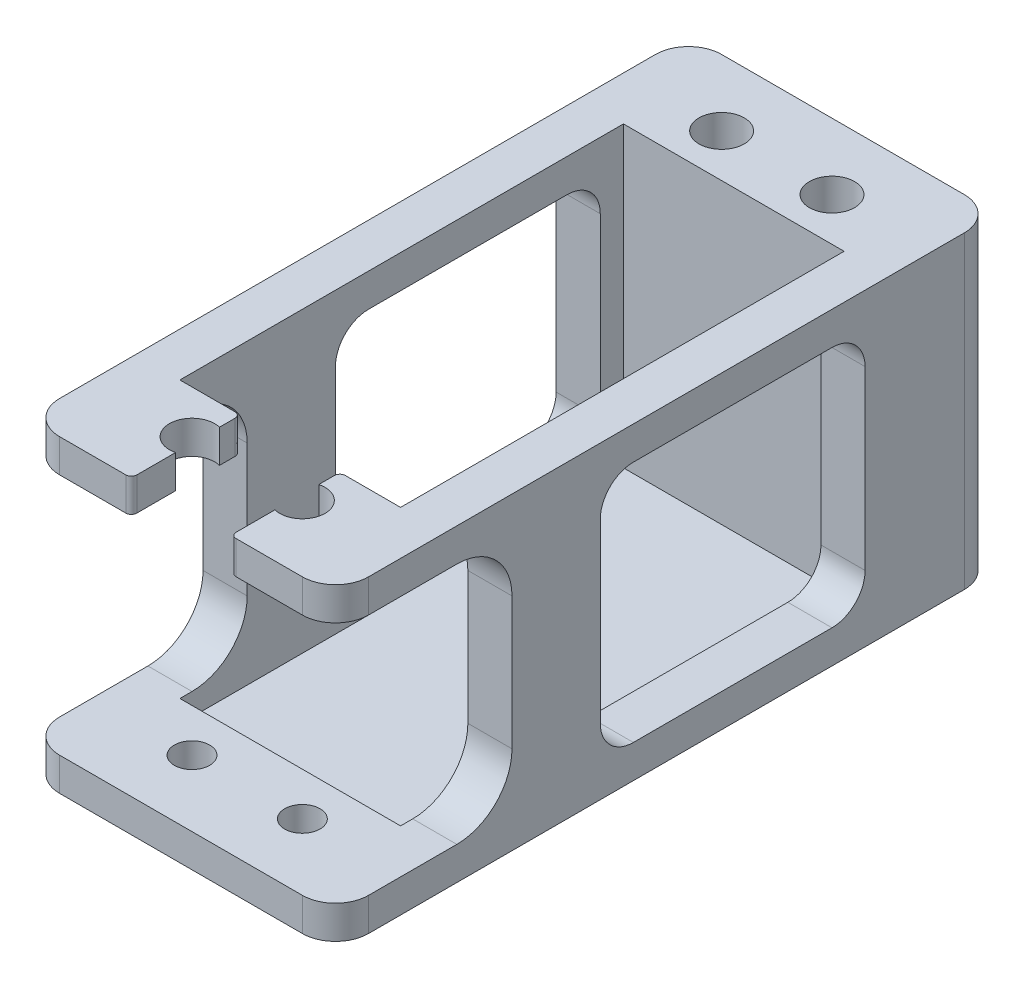
SolidWorks part; units mm, degrees
ref_plane "前视基准面" through (0, 0, 0) normal (0, 0, 1) x (1, 0, 0)
ref_plane "上视基准面" through (0, 0, 0) normal (0, 1, 0) x (1, 0, 0)
ref_plane "右视基准面" through (0, 0, 0) normal (1, 0, 0) x (0, 0, -1)
sketch "草图1" plane through (0, 0, 0) normal (0, 1, 0) x (1, 0, 0)
  line L0 (0, 0) -> (0, 29.0913) construction
  line L5 (-10, 10.2) -> (-10, -30)
  line L6 (-5, 14.1) -> (5, 14.1) construction
  line L7 (-5, 14.1) -> (-5, -33.9) construction
  line L8 (-5, -33.9) -> (5, -33.9) construction
  line L9 (5, 14.1) -> (5, -33.9) construction
  line L10 (-5, -9.9) -> (-42.4696, -9.9) construction
  line L11 (10, 10.2) -> (10, -30)
  line L12 (10, 10.2) -> (-10, 10.2)
  line L13 (10, -30) -> (-10, -30)
  line L15 (-14, -39.9) -> (14, -39.9)
  line L16 (-14, -39.9) -> (-14, 20.1)
  line L17 (-14, 20.1) -> (14, 20.1)
  line L18 (14, -39.9) -> (14, 20.1)
  line L19 (-14, -39.9) -> (14, 20.1) construction
  line L20 (-14, 20.1) -> (14, -39.9) construction
  circle A0 centre (-5, 14.1) radius 2.05
  circle A1 centre (5, 14.1) radius 2.05
  circle A2 centre (-5, -33.9) radius 2.05
  circle A3 centre (5, -33.9) radius 2.05
  point P18 (0, -9.9)
  dimension "D1" = 4.1
  dimension "D2" = 14.1
  dimension "D3" = 48
  dimension "D4" = 10
  dimension "D5" = 20
  dimension "D6" = 40.2
  dimension "D7" = 4
  dimension "D8" = 60
extrude "凸台-拉伸1" add sketch "草图1" along normal blind 28
sketch "草图4" plane through (0, 0, 0) normal (1, 0, 0) x (0, 0, -1)
  line L0 (-39.9, 28) -> (-39.9, 0) construction
  line L1 (-39.9, 25) -> (-23.9, 25)
  line L2 (-39.9, 25) -> (-39.9, 3)
  line L3 (-39.9, 3) -> (-23.9, 3)
  line L4 (-23.9, 25) -> (-23.9, 3)
  line L5 (-39.9, 28) -> (20.1, 28) construction
  line L6 (-39.9, 0) -> (20.1, 0) construction
  line L7 (20.1, 28) -> (20.1, 0) construction
  line L8 (-12.9, 25) -> (5.1, 25)
  line L9 (-15.9, 22) -> (-15.9, 6)
  line L10 (-12.9, 3) -> (5.1, 3)
  line L11 (8.1, 22) -> (8.1, 6)
  arc A0 (5.1, 25) -> (8.1, 22) centre (5.1, 22) cw
  arc A1 (-15.9, 6) -> (-12.9, 3) centre (-12.9, 6) ccw
  arc A2 (5.1, 3) -> (8.1, 6) centre (5.1, 6) ccw
  arc A3 (-12.9, 25) -> (-15.9, 22) centre (-12.9, 22) ccw
  dimension "D6" = 3
  dimension "D1" = 3
  dimension "D2" = 3
  dimension "D3" = 16
  dimension "D4" = 8
  dimension "D5" = 12
extrude "切除-拉伸3" cut sketch "草图4" against normal through all both and the other way through all
fillet "圆角3" radius 5 4 edges at (-12, 3, 23.9) (-12, 25, 23.9) (12, 3, 23.9) (12, 25, 23.9)
fillet "圆角1" radius 3 6 edges at (14, 14, -20.1) (-14, 14, -20.1) (-14, 26.5, 39.9) (-14, 1.5, 39.9) (14, 26.5, 39.9) (14, 1.5, 39.9)
sketch "草图6" plane through (0, 0, 0) normal (0, -1, 0) x (1, 0, 0)
  circle A0 centre (-5, 33.9) radius 1.6
  circle A1 centre (5, 33.9) radius 1.6
  circle A2 centre (-5, 33.9) radius 2.05 construction
  circle A3 centre (5, 33.9) radius 2.05 construction
  circle A4 centre (-5, 33.9) radius 2.05
  circle A5 centre (5, 33.9) radius 2.05
  dimension "D1" = 3.2
extrude "凸台-拉伸3" add sketch "草图6" against normal up to surface (3 mm away) up to face at (-5, 3, 31.85)
sketch "草图7" plane through (0, 28, 0) normal (0, 1, 0) x (1, 0, 0)
  line L0 (-10, -30) -> (10, -30) construction
  line L1 (-4.5, -30) -> (4.5, -30)
  line L2 (-4.5, -30) -> (-4.5, -39.9)
  line L3 (-4.5, -39.9) -> (4.5, -39.9)
  line L4 (4.5, -30) -> (4.5, -39.9)
  line L5 (-11, -39.9) -> (11, -39.9) construction
  line L6 (0, 0) -> (0, -18.3221) construction
  dimension "D1" = 9
extrude "切除-拉伸4" cut sketch "草图7" against normal up to next and the other way through all
sketch "草图9" plane through (0, 0, 0) normal (0, -1, 0) x (1, 0, 0)
  line L1 (-10, 30) -> (10, 30)
  line L2 (-10, 30) -> (-10, -10.2)
  line L3 (-10, -10.2) -> (10, -10.2)
  line L4 (10, 30) -> (10, -10.2)
extrude "凸台-拉伸4" add sketch "草图9" against normal blind 1
fillet "圆角4" radius 0.5 4 edges at (4.5, 26.5, 30) (-4.5, 26.5, 30) (4.5, 26.5, 39.9) (-4.5, 26.5, 39.9)
